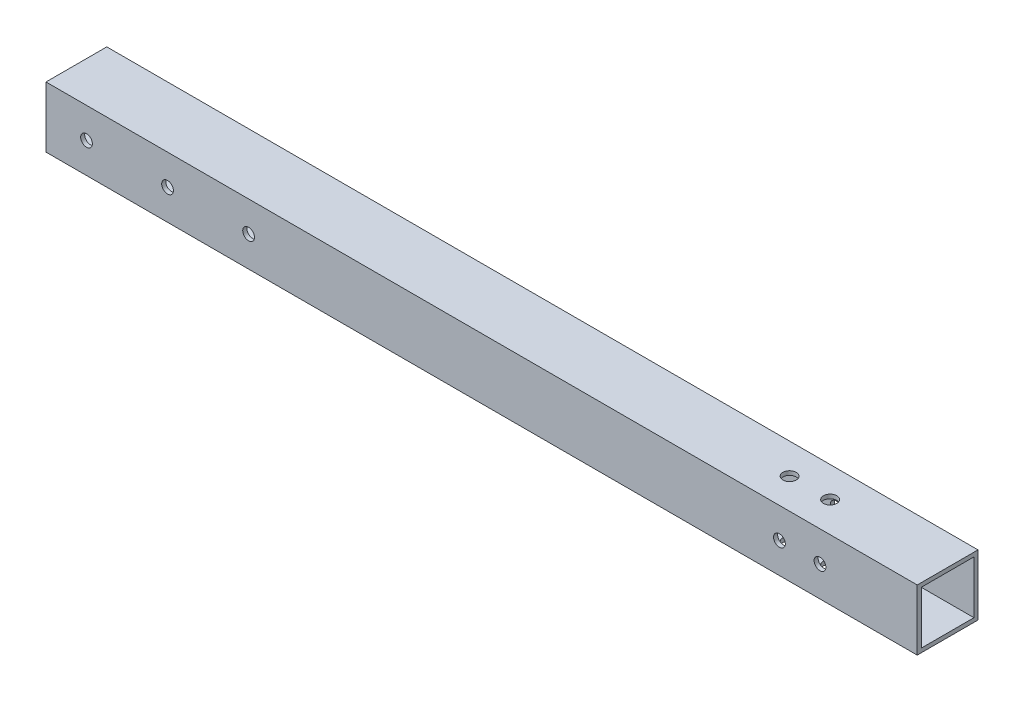
SolidWorks part; units mm, degrees
material "Thornel Mat VMA"
ref_plane "前视基准面" through (0, 0, 0) normal (0, 0, 1) x (1, 0, 0)
ref_plane "上视基准面" through (0, 0, 0) normal (0, 1, 0) x (1, 0, 0)
ref_plane "右视基准面" through (0, 0, 0) normal (1, 0, 0) x (0, 0, -1)
other "Configuration Table"
sketch "草图1" plane through (0, 0, 0) normal (1, 0, 0) x (0, 0, -1)
  line L0 (-6.5, -6.5) -> (-6.5, 6.5)
  line L1 (-7.5, -7.5) -> (7.5, -7.5)
  line L2 (-7.5, -7.5) -> (-7.5, 7.5)
  line L3 (-7.5, 7.5) -> (7.5, 7.5)
  line L4 (7.5, -7.5) -> (7.5, 7.5)
  line L5 (-7.5, -7.5) -> (7.5, 7.5) construction
  line L6 (-7.5, 7.5) -> (7.5, -7.5) construction
  line L7 (-6.5, 6.5) -> (6.5, 6.5)
  line L8 (6.5, -6.5) -> (6.5, 6.5)
  line L9 (-6.5, -6.5) -> (6.5, -6.5)
  point P0 (0, 0)
  dimension "D1" = 15
  dimension "D2" = 15
  dimension "D3" = 1
extrude "凸台-拉伸1" add sketch "草图1" along normal blind 215
sketch "草图2" plane through (0, 0, 7.5) normal (0, 0, 1) x (1, 0, 0)
  circle A0 centre (191, 0) radius 1.45 construction
  circle A1 centre (181, 0) radius 1.45 construction
  circle A2 centre (50, 0) radius 1.45 construction
  circle A3 centre (30, 0) radius 1.45 construction
  circle A4 centre (10, 0) radius 1.45 construction
  circle A5 centre (191, 0) radius 1.45
  circle A6 centre (181, 0) radius 1.45
  circle A7 centre (50, 0) radius 1.45
  circle A8 centre (30, 0) radius 1.45
  circle A9 centre (10, 0) radius 1.45
extrude "切除-拉伸1" cut sketch "草图2" against normal through all
sketch "草图3" plane through (0, 7.5, 0) normal (0, 1, 0) x (1, 0, 0)
  circle A0 centre (176, 0) radius 1.65 construction
  circle A1 centre (186, 0) radius 1.65 construction
  circle A2 centre (176, 0) radius 1.65
  circle A3 centre (186, 0) radius 1.65
extrude "切除-拉伸2" cut sketch "草图3" against normal through all
